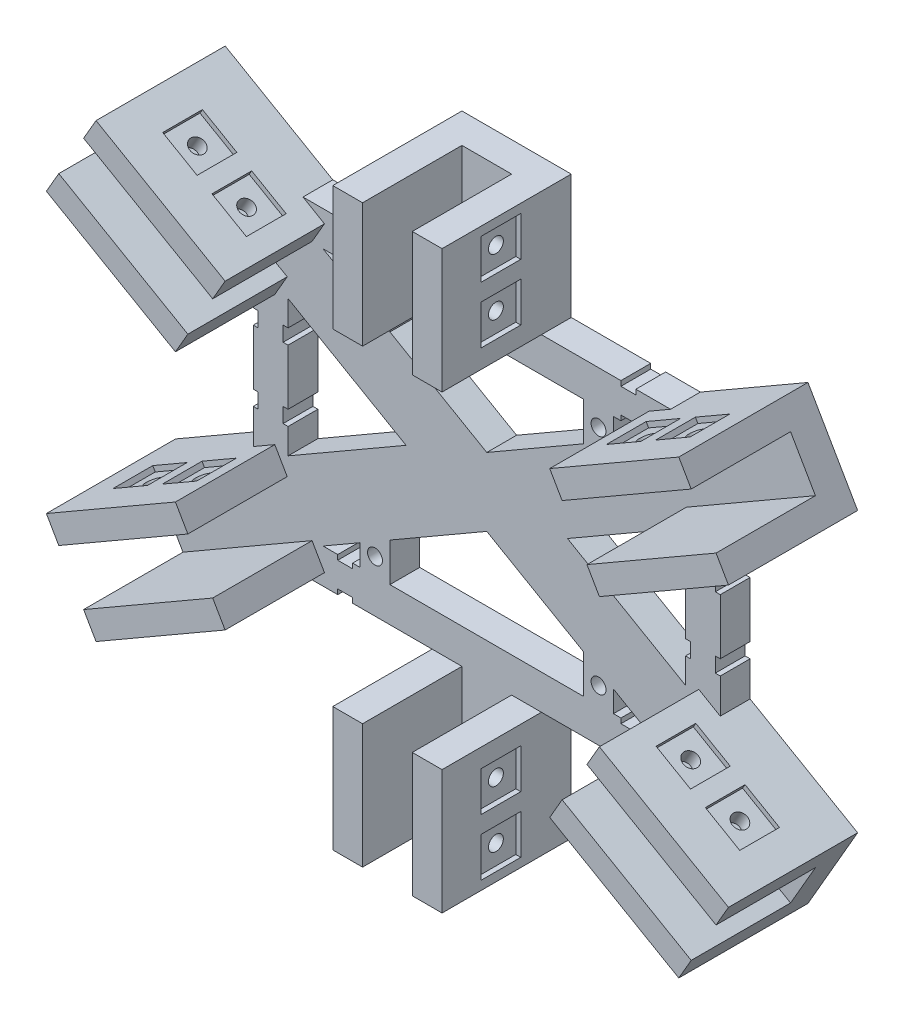
SolidWorks part; units mm, degrees
ref_plane "Plan de face" through (0, 0, 0) normal (0, 0, 1) x (1, 0, 0)
ref_plane "Plan de dessus" through (0, 0, 0) normal (0, 1, 0) x (1, 0, 0)
ref_plane "Plan de droite" through (0, 0, 0) normal (1, 0, 0) x (0, 0, -1)
sketch "Esquisse1" plane through (0, 0, 0) normal (0, 0, 1) x (1, 0, 0)
  line L1 (-27, -32.909) -> (-27, -31.909)
  line L2 (-27, -31.909) -> (-30, -31.909)
  line L3 (-30, -31.909) -> (-30, -32.909)
  line L4 (-30, -32.909) -> (-37, -32.909)
  line L5 (89.9983, 57.7339) -> (33.4379, 25.0787) construction
  line L6 (-47, -15.5885) -> (-47, -8.5885)
  line L7 (-47, -8.5885) -> (-46, -8.5885)
  line L8 (-46, -8.5885) -> (-46, -5.5885)
  line L9 (-46, -5.5885) -> (-47, -5.5885)
  line L10 (-47, -5.5885) -> (-47, 5.5885)
  line L11 (0, -32.909) -> (0, 32.909) construction
  line L12 (40, 0) -> (-40, 0) construction
  line L13 (-42, -24.2487) -> (0, 0) construction
  line L14 (-40, 5.5885) -> (-40, -5.5885)
  line L15 (-40, -5.5885) -> (-41, -5.5885)
  line L16 (-41, -5.5885) -> (-41, -8.5885)
  line L17 (-41, -8.5885) -> (-40, -8.5885)
  line L18 (-40, -8.5885) -> (-40, -13.7128)
  line L19 (40, 13.7128) -> (16.2487, 0)
  line L20 (-32.9585, -25.909) -> (-30, -25.909)
  line L21 (-30, -25.909) -> (-30, -26.909)
  line L22 (-30, -26.909) -> (-27, -26.909)
  line L23 (-27, -26.909) -> (-27, -25.909)
  line L24 (58.6507, 45.4089) -> (37.0001, 32.9089)
  line L25 (-42, 24.2487) -> (0, 0) construction
  line L26 (19.5, -25.909) -> (0, -25.909)
  line L27 (-27, 26.909) -> (-27, 25.909)
  line L28 (-30, 26.909) -> (-27, 26.909)
  line L29 (-30, 25.909) -> (-30, 26.909)
  line L30 (-32.9585, 25.909) -> (-30, 25.909)
  line L31 (-40, 13.7128) -> (-16.2487, 0)
  line L32 (-40, 8.5885) -> (-40, 13.7128)
  line L33 (-41, 8.5885) -> (-40, 8.5885)
  line L34 (-41, 5.5885) -> (-41, 8.5885)
  line L35 (-40, 5.5885) -> (-41, 5.5885)
  line L36 (-46, 5.5885) -> (-47, 5.5885)
  line L37 (-46, 8.5885) -> (-46, 5.5885)
  line L38 (-47, 8.5885) -> (-46, 8.5885)
  line L39 (-47, 15.5885) -> (-47, 8.5885)
  line L40 (-58.6507, 45.4089) -> (-37.0001, 32.9089)
  line L41 (-30, 32.909) -> (-37, 32.909)
  line L42 (-30, 31.909) -> (-30, 32.909)
  line L43 (-27, 31.909) -> (-30, 31.909)
  line L44 (-27, 32.909) -> (-27, 31.909)
  line L45 (-27, 32.909) -> (-11, 32.909)
  line L46 (42, 24.2487) -> (0, 0) construction
  line L47 (42, -24.2487) -> (0, 0) construction
  line L48 (27, 32.909) -> (27, 31.909)
  line L49 (27, 31.909) -> (30, 31.909)
  line L50 (30, 31.909) -> (30, 32.909)
  line L51 (30, 32.909) -> (37, 32.909)
  line L52 (-47.0001, 15.5883) -> (-47, 15.5885)
  line L53 (47, 15.5885) -> (47, 8.5885)
  line L54 (47, 8.5885) -> (46, 8.5885)
  line L55 (46, 8.5885) -> (46, 5.5885)
  line L56 (46, 5.5885) -> (47, 5.5885)
  line L57 (40, 5.5885) -> (41, 5.5885)
  line L58 (41, 5.5885) -> (41, 8.5885)
  line L59 (41, 8.5885) -> (40, 8.5885)
  line L60 (40, 8.5885) -> (40, 13.7128)
  line L61 (32.9585, 25.909) -> (25.5, 21.6028)
  line L62 (32.9585, 25.909) -> (30, 25.909)
  line L63 (30, 25.909) -> (30, 26.909)
  line L64 (30, 26.909) -> (27, 26.909)
  line L65 (27, 26.909) -> (27, 25.909)
  line L66 (27, -26.909) -> (27, -25.909)
  line L67 (30, -26.909) -> (27, -26.909)
  line L68 (30, -25.909) -> (30, -26.909)
  line L69 (32.9585, -25.909) -> (30, -25.909)
  line L70 (-32.9585, 25.909) -> (-25.5, 21.6028)
  line L71 (40, -8.5885) -> (40, -13.7128)
  line L72 (41, -8.5885) -> (40, -8.5885)
  line L73 (41, -5.5885) -> (41, -8.5885)
  line L74 (40, -5.5885) -> (41, -5.5885)
  line L75 (40, 5.5885) -> (40, -5.5885)
  line L76 (47, -5.5885) -> (47, 5.5885)
  line L77 (46, -5.5885) -> (47, -5.5885)
  line L78 (46, -8.5885) -> (46, -5.5885)
  line L79 (47, -8.5885) -> (46, -8.5885)
  line L80 (47, -15.5885) -> (47, -8.5885)
  line L81 (-37, 32.909) -> (-37.0001, 32.9089)
  line L82 (30, -32.909) -> (37, -32.909)
  line L83 (30, -31.909) -> (30, -32.909)
  line L84 (27, -31.909) -> (30, -31.909)
  line L85 (27, -32.909) -> (27, -31.909)
  line L86 (40, -13.7128) -> (16.2487, 0)
  line L87 (-25.5, 25.909) -> (-25.5, 21.6028)
  line L88 (-19.5, 25.909) -> (-19.5, 18.1387)
  line L89 (-40, -13.7128) -> (-16.2487, 0)
  line L90 (25.5, 25.909) -> (25.5, 21.6028)
  line L91 (19.5, 25.909) -> (19.5, 18.1387)
  line L92 (19.5, 18.1387) -> (0, 6.8803)
  line L93 (-19.5, 18.1387) -> (0, 6.8803)
  line L94 (-32.9585, -25.909) -> (-25.5, -21.6028)
  line L95 (-25.5, -25.909) -> (-25.5, -21.6028)
  line L96 (-19.5, -25.909) -> (-19.5, -18.1387)
  line L97 (-19.5, -18.1387) -> (0, -6.8803)
  line L98 (32.9585, -25.909) -> (25.5, -21.6028)
  line L99 (25.5, -25.909) -> (25.5, -21.6028)
  line L100 (19.5, -25.909) -> (19.5, -18.1387)
  line L101 (19.5, -18.1387) -> (0, -6.8803)
  line L102 (27, 25.909) -> (25.5, 25.909)
  line L103 (19.5, 25.909) -> (0, 25.909)
  line L104 (0, 25.909) -> (-19.5, 25.909)
  line L105 (-25.5, 25.909) -> (-27, 25.909)
  line L106 (0, -25.909) -> (-19.5, -25.909)
  line L107 (-25.5, -25.909) -> (-27, -25.909)
  line L108 (27, -25.909) -> (25.5, -25.909)
  line L109 (68.6507, 28.0883) -> (58.6507, 45.4089)
  line L110 (68.6507, 28.0883) -> (47.0001, 15.5883)
  line L111 (37, 32.909) -> (37.0001, 32.9089)
  line L112 (47.0001, 15.5883) -> (47, 15.5885)
  line L113 (-68.6507, 28.0883) -> (-47.0001, 15.5883)
  line L114 (-68.6507, 28.0883) -> (-58.6507, 45.4089)
  line L115 (-11, 32.909) -> (-11, 57.909)
  line L116 (-11, 57.909) -> (11, 57.909)
  line L117 (37, -32.909) -> (37.0001, -32.9089)
  line L118 (47.0001, -15.5883) -> (47, -15.5885)
  line L119 (68.6507, -28.0883) -> (47.0001, -15.5883)
  line L120 (68.6507, -28.0883) -> (58.6507, -45.4089)
  line L121 (58.6507, -45.4089) -> (37.0001, -32.9089)
  line L122 (-37, -32.909) -> (-37.0001, -32.9089)
  line L123 (-47.0001, -15.5883) -> (-47, -15.5885)
  line L124 (-68.6507, -28.0883) -> (-58.6507, -45.4089)
  line L125 (-68.6507, -28.0883) -> (-47.0001, -15.5883)
  line L126 (-58.6507, -45.4089) -> (-37.0001, -32.9089)
  line L127 (11, 57.909) -> (11, 32.909)
  line L128 (11, 32.909) -> (27, 32.909)
  line L129 (11, -32.909) -> (27, -32.909)
  line L130 (-27, -32.909) -> (-11, -32.909)
  line L131 (-11, -32.909) -> (-11, -57.909)
  line L132 (11, -57.909) -> (11, -32.909)
  line L133 (-11, -57.909) -> (11, -57.909)
  circle A0 centre (22.5, 22.5) radius 1.5
  circle A1 centre (-22.5, 22.5) radius 1.5
  circle A2 centre (22.5, -22.5) radius 1.5
  circle A3 centre (-22.5, -22.5) radius 1.5
  point P10 (-42, -24.2487)
  point P41 (-47, 0)
  point P73 (0, 25.909)
  point P74 (0, -25.909)
  point P75 (0, -25.909)
  point P94 (47, 0)
  dimension "D13" = 2
  dimension "D1" = 1
  dimension "D2" = 3
  dimension "D3" = 7
  dimension "D4" = 3
  dimension "D5" = 7
  dimension "D6" = 60
  dimension "D7" = 20
  dimension "D8" = 1
  dimension "D9" = 1
  dimension "D10" = 1
  dimension "D11" = 7
  dimension "D12" = 3
  dimension "D14" = 20
  dimension "D15" = 30
  dimension "D16" = 2
  dimension "D17" = 22.5
  dimension "D18" = 22.5
  dimension "D19" = 3
  dimension "D20" = 90
  dimension "D21" = 90
  dimension "D22" = 5
  dimension "D23" = 11
  dimension "D24" = 11
  dimension "D25" = 25
extrude "Boss.-Extru.2" add sketch "Esquisse1" along normal blind 6
sketch "Esquisse4" plane through (0, 0, 0) normal (0, 0, -1) x (-1, 0, 0)
  line L1 (-22.4277, 19.6872) -> (-20.0279, 21.1562)
  line L2 (-20.0279, 21.1562) -> (-20.1002, 23.969)
  line L3 (-20.1002, 23.969) -> (-22.5723, 25.3128)
  line L4 (-22.5723, 25.3128) -> (-24.9721, 23.8438)
  line L5 (-24.9721, 23.8438) -> (-24.8998, 21.031)
  line L6 (-24.8998, 21.031) -> (-22.4277, 19.6872)
  line L7 (0, -32.2873) -> (0, 32.2873) construction
  line L8 (43.6304, 0) -> (-43.6304, 0) construction
  line L9 (0, -32.909) -> (0, 32.909) construction
  line L10 (-40, 0) -> (40, 0) construction
  line L11 (24.8998, 21.031) -> (22.4277, 19.6872)
  line L12 (24.9721, 23.8438) -> (24.8998, 21.031)
  line L13 (22.5723, 25.3128) -> (24.9721, 23.8438)
  line L14 (20.1002, 23.969) -> (22.5723, 25.3128)
  line L15 (20.0279, 21.1562) -> (20.1002, 23.969)
  line L16 (22.4277, 19.6872) -> (20.0279, 21.1562)
  line L17 (22.4277, -19.6872) -> (20.0279, -21.1562)
  line L18 (20.0279, -21.1562) -> (20.1002, -23.969)
  line L19 (20.1002, -23.969) -> (22.5723, -25.3128)
  line L20 (22.5723, -25.3128) -> (24.9721, -23.8438)
  line L21 (24.9721, -23.8438) -> (24.8998, -21.031)
  line L22 (24.8998, -21.031) -> (22.4277, -19.6872)
  line L23 (-24.8998, -21.031) -> (-22.4277, -19.6872)
  line L24 (-24.9721, -23.8438) -> (-24.8998, -21.031)
  line L25 (-22.5723, -25.3128) -> (-24.9721, -23.8438)
  line L26 (-20.1002, -23.969) -> (-22.5723, -25.3128)
  line L27 (-20.0279, -21.1562) -> (-20.1002, -23.969)
  line L28 (-22.4277, -19.6872) -> (-20.0279, -21.1562)
  circle A0 centre (-22.5, 22.5) radius 2.4368 construction
  circle A1 centre (22.5, 22.5) radius 2.4368 construction
  circle A2 centre (22.5, -22.5) radius 2.4368 construction
  circle A3 centre (-22.5, -22.5) radius 2.4368 construction
extrude "Enlèv. mat.-Extru.2" cut sketch "Esquisse4" against normal blind 2
sketch "Esquisse5" plane through (63.6506, 36.7487, 0) normal (0.866, 0.5, 0) x (0, 0, -1)
  line L0 (-6, -10.0001) -> (-6, -5.0001)
  line L1 (-6, -10.0001) -> (-6, 9.9999) construction
  line L2 (-6, -5.0001) -> (-26, -5.0001)
  line L3 (-26, -5.0001) -> (-26, -10.0001)
  line L4 (-26, -10.0001) -> (-6, -10.0001)
  dimension "D1" = 20
  dimension "D2" = 5
extrude "Boss.-Extru.3" add sketch "Esquisse5" against normal blind 30
sketch "Esquisse7" plane through (63.6506, 36.7487, 0) normal (0.866, 0.5, 0) x (0, 0, -1)
  line L0 (-6, 4.9999) -> (-6, 9.9999)
  line L2 (-6, 9.9999) -> (-26, 9.9999)
  line L3 (-26, 9.9999) -> (-26, 4.9999)
  line L4 (-26, 4.9999) -> (-6, 4.9999)
  line L5 (-6, -5.0001) -> (-6, 9.9999) construction
  dimension "D1" = 20
  dimension "D2" = 5
extrude "Boss.-Extru.4" add sketch "Esquisse7" against normal blind 30
sketch "Esquisse8" plane through (5.0001, -8.6604, 0) normal (0.5, -0.866, 0) x (0.866, 0.5, 0)
  line L1 (47.611, 18.1555) -> (55.611, 18.1555)
  line L2 (47.611, 18.1555) -> (47.611, 10.1555)
  line L3 (47.611, 10.1555) -> (55.611, 10.1555)
  line L4 (55.611, 18.1555) -> (55.611, 10.1555)
  dimension "D1" = 8
  dimension "D2" = 8
extrude "Enlèv. mat.-Extru.3" cut sketch "Esquisse8" against normal blind 1
sketch "Esquisse9" plane through (5.0001, -8.6604, 0) normal (0.5, -0.866, 0) x (0.866, 0.5, 0)
  line L0 (55.611, 18.1555) -> (47.611, 18.1555) construction
  line L1 (59.0628, 18.1555) -> (67.0628, 18.1555)
  line L2 (59.0628, 18.1555) -> (59.0628, 10.1555)
  line L3 (59.0628, 10.1555) -> (67.0628, 10.1555)
  line L4 (67.0628, 18.1555) -> (67.0628, 10.1555)
  dimension "D1" = 8
  dimension "D2" = 8
extrude "Enlèv. mat.-Extru.4" cut sketch "Esquisse9" against normal blind 1
ref_plane "Plan8" through (0.0001, -0.0001, 0) normal (-0.5, 0.866, 0) x (-0.866, -0.5, 0)
sketch "Esquisse10" plane through (4.5001, -7.7943, 0) normal (0.5, -0.866, 0) x (0.866, 0.5, 0)
  line L3 (55.611, 18.1555) -> (47.611, 18.1555) construction
  line L4 (47.611, 18.1555) -> (47.611, 10.1555) construction
  circle A0 centre (51.611, 14.1555) radius 1.5
  point P2 (51.611, 18.1555)
  point P3 (47.611, 14.1555)
extrude "Enlèv. mat.-Extru.5" cut sketch "Esquisse10" against normal blind 3
ref_plane "Plan9" through (49.6552, 28.6684, 0) normal (-0.866, -0.5, 0) x (0, 0, 1)
mirror "Symétrie4" about plane through (49.6552, 28.6684, 0) normal (-0.866, -0.5, 0) of "Enlèv. mat.-Extru.5"
mirror "Symétrie5" about plane through (0.0001, -0.0001, 0) normal (-0.5, 0.866, 0) of "Enlèv. mat.-Extru.3", "Enlèv. mat.-Extru.4", "Enlèv. mat.-Extru.5", "Symétrie4"
mirror "Symétrie7" about plane through (0, 0, 0) normal (0, 1, 0) of "Boss.-Extru.3", "Boss.-Extru.4", "Enlèv. mat.-Extru.3", "Enlèv. mat.-Extru.4", "Enlèv. mat.-Extru.5", "Symétrie4", "Symétrie5"
mirror "Symétrie8" about plane through (0, 0, 0) normal (1, 0, 0) of "Boss.-Extru.3", "Boss.-Extru.4", "Enlèv. mat.-Extru.3", "Enlèv. mat.-Extru.4", "Symétrie5", "Symétrie4", "Enlèv. mat.-Extru.5", "Symétrie7"
sketch "Esquisse11" plane through (0, 57.909, 0) normal (0, 1, 0) x (1, 0, 0)
  line L6 (-11, -6) -> (-5, -6)
  line L7 (-11, -6) -> (-11, -26)
  line L8 (-11, -26) -> (-5, -26)
  line L9 (-5, -6) -> (-5, -26)
  dimension "D1" = 6
  dimension "D2" = 20
extrude "Boss.-Extru.5" add sketch "Esquisse11" against normal blind 25
sketch "Esquisse50" plane through (-11, 26.5177, -42.9653) normal (-1, 0, 0) x (0, 0, 1)
  line L0 (42.9653, 31.3912) -> (42.9653, 6.3912) construction
  line L1 (53.1253, 18.1555) -> (61.1253, 18.1555)
  line L2 (53.1253, 18.1555) -> (53.1253, 10.1555)
  line L3 (53.1253, 10.1555) -> (61.1253, 10.1555)
  line L4 (61.1253, 18.1555) -> (61.1253, 10.1555)
  dimension "D1" = 8
  dimension "D2" = 8
  dimension "D3" = 10.16
extrude "Enlèv. mat.-Extru.25" cut sketch "Esquisse50" against normal blind 1
sketch "Esquisse52" plane through (-11, 26.5177, -42.9653) normal (-1, 0, 0) x (0, 0, 1)
  line L0 (53.1253, 18.1555) -> (53.1253, 10.1555) construction
  line L1 (53.1253, 29.6055) -> (61.1253, 29.6055)
  line L2 (53.1253, 29.6055) -> (53.1253, 21.6055)
  line L3 (53.1253, 21.6055) -> (61.1253, 21.6055)
  line L4 (61.1253, 29.6055) -> (61.1253, 21.6055)
  line L6 (61.1253, 18.1555) -> (53.1253, 18.1555) construction
  dimension "D1" = 8
  dimension "D2" = 8
  dimension "D3" = 3.45
extrude "Enlèv. mat.-Extru.26" cut sketch "Esquisse52" against normal blind 1
sketch "Esquisse54" plane through (-10, 26.5177, -42.9653) normal (-1, 0, 0) x (0, 0, 1)
  line L3 (61.1253, 18.1555) -> (53.1253, 18.1555) construction
  line L4 (53.1253, 18.1555) -> (53.1253, 10.1555) construction
  circle A0 centre (57.1253, 14.1555) radius 1.5
  point P2 (57.1253, 18.1555)
  point P3 (53.1253, 14.1555)
extrude "Enlèv. mat.-Extru.27" cut sketch "Esquisse54" against normal blind 3
ref_plane "Plan14" through (0, 46.3982, 0) normal (0, 1, 0) x (-1, 0, 0)
mirror "Symétrie9" about plane through (0, 46.3982, 0) normal (0, 1, 0) of "Enlèv. mat.-Extru.27"
ref_plane "Plan17" through (0, 0, 0) normal (-1, 0, 0) x (0, 0, 1)
mirror "Symétrie10" about plane through (0, 0, 0) normal (-1, 0, 0) of "Symétrie9", "Enlèv. mat.-Extru.27", "Enlèv. mat.-Extru.26", "Enlèv. mat.-Extru.25", "Boss.-Extru.5"
mirror "Symétrie11" about plane through (0, 0, 0) normal (0, 1, 0) of "Symétrie10", "Symétrie9", "Enlèv. mat.-Extru.27", "Enlèv. mat.-Extru.26", "Enlèv. mat.-Extru.25", "Boss.-Extru.5"
